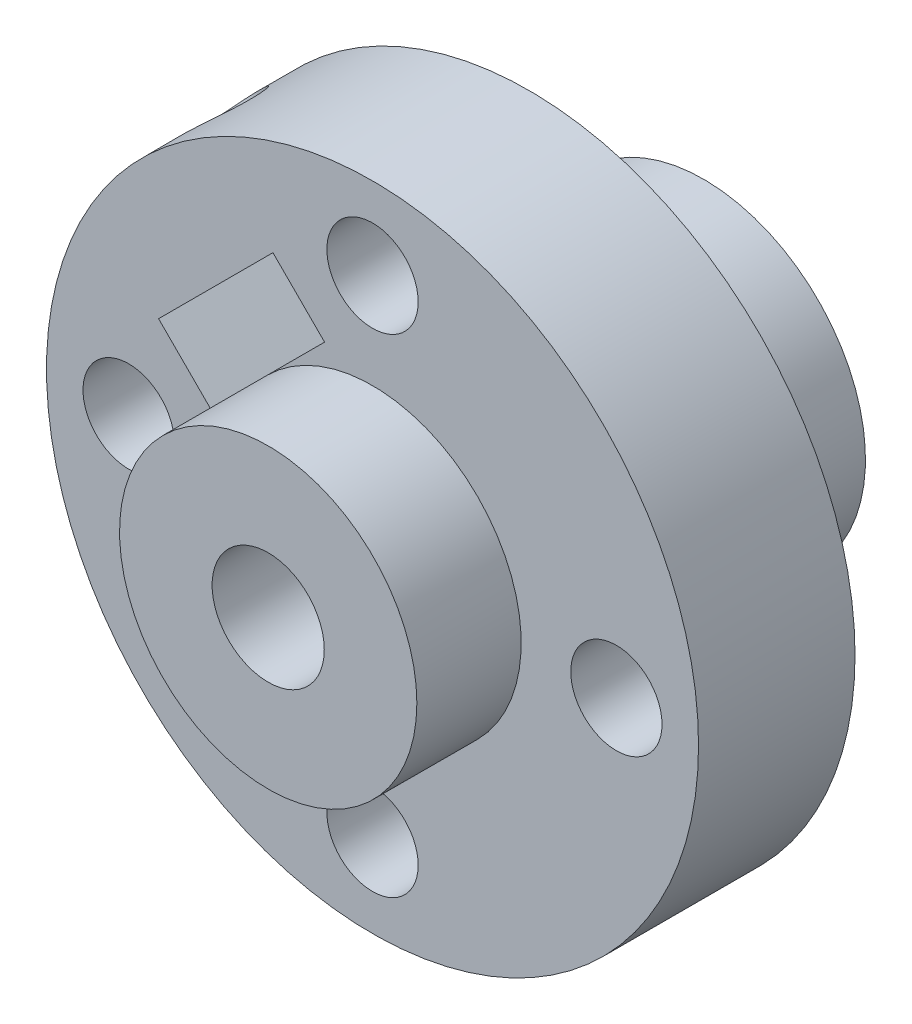
SolidWorks part; units mm, degrees
ref_plane "Plano frontal" through (0, 0, 0) normal (0, 0, 1) x (1, 0, 0)
ref_plane "Plano superior" through (0, 0, 0) normal (0, 1, 0) x (1, 0, 0)
ref_plane "Plano direito" through (0, 0, 0) normal (1, 0, 0) x (0, 0, -1)
sketch "Esboço1" plane through (0, 0, 0) normal (0, 0, 1) x (1, 0, 0)
  circle A0 centre (-38.3545, 25.4713) radius 12.5
extrude "Ressalto-extrusão1" add sketch "Esboço1" along normal blind 6
sketch "Esboço5" plane through (0, 0, 0) normal (0, 0, -1) x (-1, 0, 0)
  circle A0 centre (38.3545, 25.4713) radius 6.2
extrude "Ressalto-extrusão2" add sketch "Esboço5" along normal blind 6.7
sketch "Esboço6" plane through (0, 0, 6) normal (0, 0, 1) x (1, 0, 0)
  circle A0 centre (-38.3545, 25.4713) radius 5.7
  dimension "D1" = 11.4
extrude "Ressalto-extrusão3" add sketch "Esboço6" along normal blind 4
sketch "Esboço7" plane through (0, 0, 10) normal (0, 0, 1) x (1, 0, 0)
  circle A0 centre (-38.3545, 25.4713) radius 2.15
  dimension "D1" = 4.3
extrude "Corte-extrusão1" cut sketch "Esboço7" against normal blind 13.95
sketch "Esboço9" plane through (0, 0, 6) normal (0, 0, 1) x (1, 0, 0)
  line L0 (-44.5771, 27.3098) -> (-40.193, 31.6939)
  line L7 (-42.1729, 33.6738) -> (-40.193, 31.6939)
  line L8 (-46.557, 29.2897) -> (-42.1729, 33.6738)
  line L9 (-46.557, 29.2897) -> (-44.5771, 27.3098)
  point P12 (-38.3545, 25.4713)
  dimension "D1" = 2.8
  dimension "D2" = 6.2
  dimension "D3" = 5.7
sketch "Esboço10" plane through (0, 0, 6) normal (0, 0, 1) x (1, 0, 0)
  line L0 (-38.3545, 37.9713) -> (-38.3545, 12.9713) construction
  line L1 (-25.8545, 25.4713) -> (-50.8545, 25.4713) construction
  circle A0 centre (-38.3545, 34.8213) radius 1.75
  circle A1 centre (-38.3545, 25.4713) radius 12.5 construction
  circle A2 centre (-38.3545, 16.1213) radius 1.75
  circle A3 centre (-29.0045, 25.4713) radius 1.75
  circle A4 centre (-47.7045, 25.4713) radius 1.75
  dimension "D1" = 9.35
  dimension "D2" = 9.35
extrude "Corte-extrusão2" cut sketch "Esboço10" against normal through all
extrude "Corte-extrusão3" cut sketch "Esboço9" against normal blind 6
sketch "Esboço12" plane through (-37.9233, 37.9233, 0) normal (0.7071, -0.7071, 0) x (0, 0, -1)
  line L0 (-6, -6.0098) -> (-6, -12.2098) construction
  circle A0 centre (-3, -9.1098) radius 1.5
  dimension "D1" = 3
extrude "Corte-extrusão4" cut sketch "Esboço12" against normal up to next and the other way up to next
